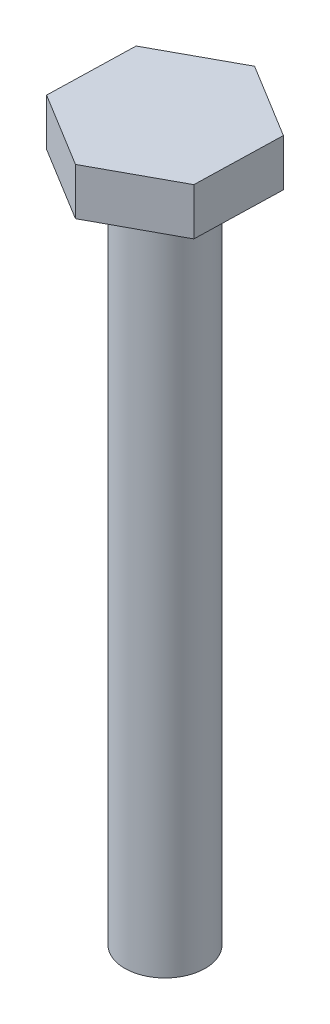
SolidWorks part; units mm, degrees
ref_plane "Front Plane" through (0, 0, 0) normal (0, 0, 1) x (1, 0, 0)
ref_plane "Top Plane" through (0, 0, 0) normal (0, 1, 0) x (1, 0, 0)
ref_plane "Right Plane" through (0, 0, 0) normal (1, 0, 0) x (0, 0, -1)
sketch "Sketch1" plane through (0, 0, 0) normal (0, 1, 0) x (1, 0, 0)
  line L1 (5.5434, -3.3943) -> (5.7112, 3.1035)
  line L2 (5.7112, 3.1035) -> (0.1679, 6.4978)
  line L3 (0.1679, 6.4978) -> (-5.5434, 3.3943)
  line L4 (-5.5434, 3.3943) -> (-5.7112, -3.1035)
  line L5 (-5.7112, -3.1035) -> (-0.1679, -6.4978)
  line L6 (-0.1679, -6.4978) -> (5.5434, -3.3943)
  circle A0 centre (0, 0) radius 5.6292 construction
extrude "Boss-Extrude1" add sketch "Sketch1" along normal blind 3.5
sketch "Sketch2" plane through (0, 0, 0) normal (0, -1, 0) x (1, 0, 0)
  circle A0 centre (0, 0) radius 3
extrude "Boss-Extrude2" add sketch "Sketch2" along normal blind 50
